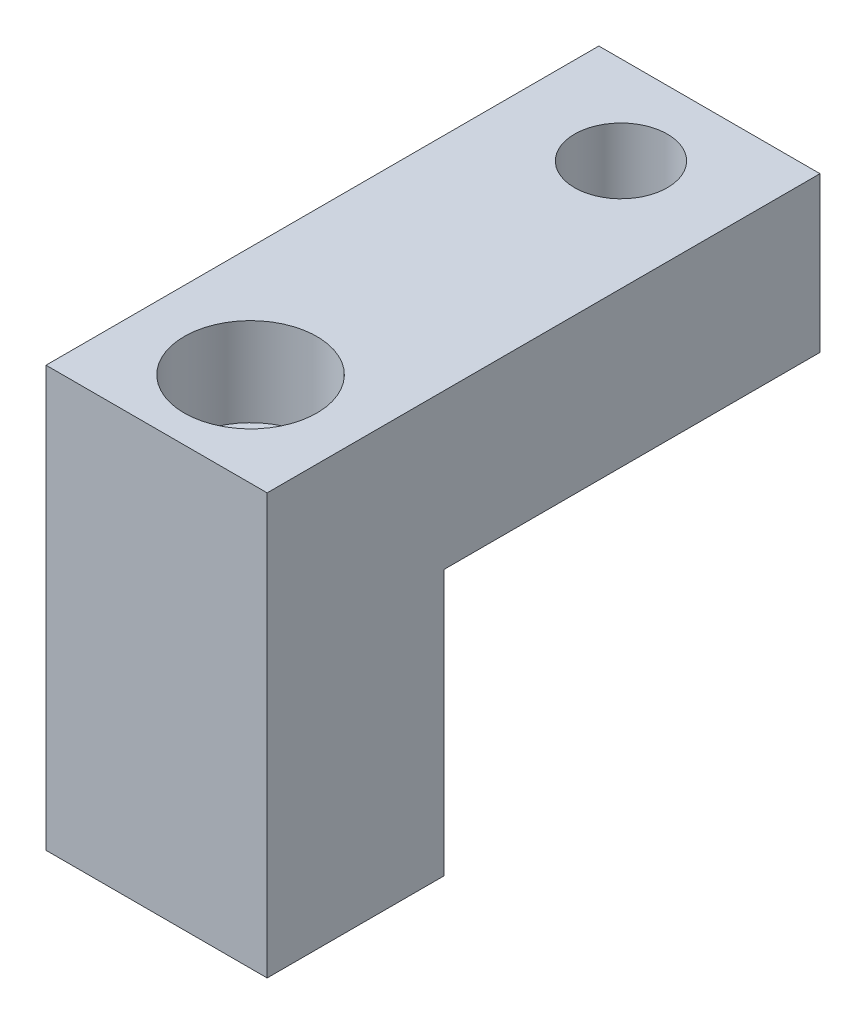
SolidWorks part; units mm, degrees
ref_plane "Front Plane" through (0, 0, 0) normal (0, 0, 1) x (1, 0, 0)
ref_plane "Top Plane" through (0, 0, 0) normal (0, 1, 0) x (1, 0, 0)
ref_plane "Right Plane" through (0, 0, 0) normal (1, 0, 0) x (0, 0, -1)
sketch "Sketch1" plane through (0, 0, 0) normal (0, 1, 0) x (1, 0, 0)
  line L1 (0, 0) -> (10, 0)
  line L2 (0, 0) -> (0, 25)
  line L3 (0, 25) -> (10, 25)
  line L4 (10, 0) -> (10, 25)
  circle A0 centre (5, 21) radius 2.1
  point P7 (5, 25)
  dimension "D3" = 4.2
  dimension "D4" = 4
  dimension "D1" = 10
  dimension "D2" = 25
extrude "Boss-Extrude1" add sketch "Sketch1" along normal blind 7
sketch "Sketch2" plane through (0, 0, 0) normal (0, -1, 0) x (-1, 0, 0)
  line L0 (-10, 0) -> (-10, 25) construction
  line L1 (0, 0) -> (-10, 0)
  line L2 (0, 0) -> (0, 8)
  line L3 (0, 8) -> (-10, 8)
  line L4 (-10, 0) -> (-10, 8)
  dimension "D1" = 8
extrude "Boss-Extrude2" add sketch "Sketch2" along normal blind 12
sketch "Sketch3" plane through (0, 7, 0) normal (0, 1, 0) x (1, 0, 0)
  line L0 (0, 0) -> (10, 0) construction
  circle A0 centre (5, 4.25) radius 1.7
  circle A1 centre (5, 21) radius 2.1 construction
  point P4 (5, 0)
  dimension "D1" = 3.4
  dimension "the_length" = 16.75
extrude "Cut-Extrude1" cut sketch "Sketch3" against normal through all
sketch "Sketch4" plane through (0, 7, 0) normal (0, 1, 0) x (1, 0, 0)
  circle A0 centre (5, 4.25) radius 3
  dimension "D1" = 6
extrude "Cut-Extrude2" cut sketch "Sketch4" against normal blind 4
